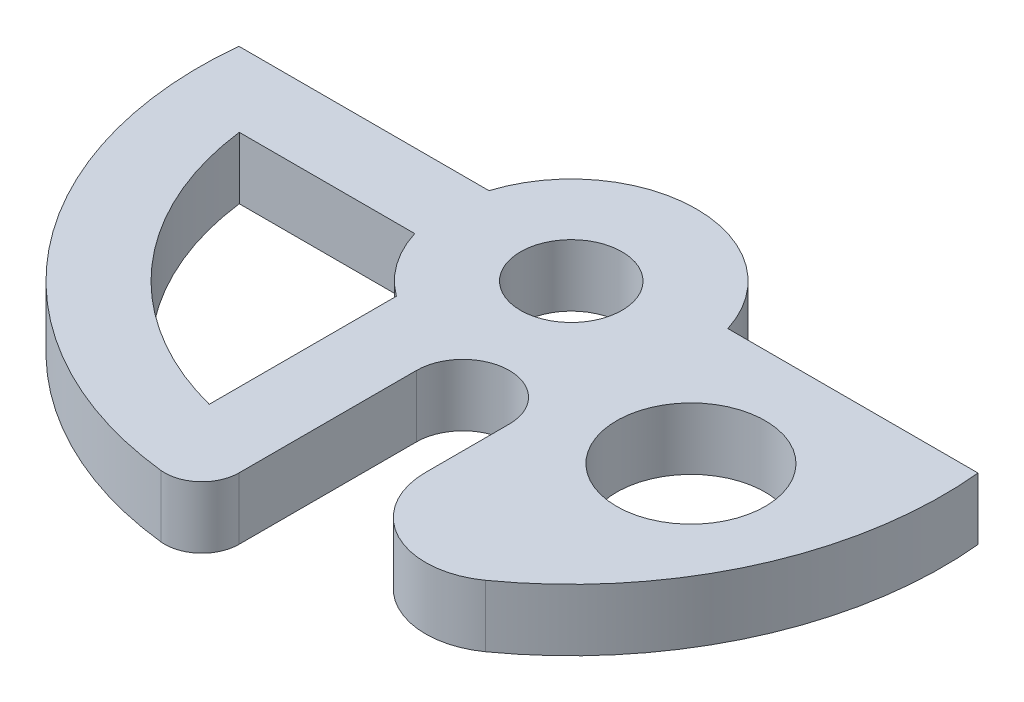
SolidWorks part; units mm, degrees
ref_plane "Front Plane" through (0, 0, 0) normal (0, 0, 1) x (1, 0, 0)
ref_plane "Top Plane" through (0, 0, 0) normal (0, 1, 0) x (1, 0, 0)
ref_plane "Right Plane" through (0, 0, 0) normal (1, 0, 0) x (0, 0, -1)
sketch "Sketch1" plane through (0, 0, 0) normal (0, 1, 0) x (1, 0, 0)
  line L0 (0, -12.5) -> (0, -30)
  line L1 (0, 0) -> (13.8, -19.2678) construction
  line L2 (0, 0) -> (0, -30) construction
  line L3 (7.5, -12.5) -> (7.5, -30)
  circle A0 centre (0, 0) radius 30
  circle A1 centre (13.8, -19.2678) radius 6.3
  circle A2 centre (3.75, -12.5) radius 3.75
  circle A3 centre (0, 0) radius 4.1
  dimension "D1" = 60
  dimension "D2" = 12.6
  dimension "D5" = 8.2
  dimension "D3" = 17.5
  dimension "D4" = 7.5
extrude "Boss-Extrude1" add sketch "Sketch1" along normal blind 5 contours A2 L3 A1 A0 L0 A3 | A1
fillet "Fillet1" radius 3 1 edges at (0, 2.5, 30)
sketch "Sketch2" plane through (0, 5, 0) normal (0, 1, 0) x (1, 0, 0)
  line L0 (0, -24) -> (0, -10.1)
  line L1 (-6, -24) -> (-6, -8.1247)
  line L2 (-6, -24) -> (-6, -10.1) construction
  line L3 (-24, 0) -> (24, 0) construction
  line L4 (-24, -3) -> (24, -3)
  line L5 (-24, 3) -> (24, 3)
  line L6 (24, 3) -> (35.1662, 3)
  line L7 (-24, 3) -> (-33.0695, 3)
  circle A0 centre (0, 0) radius 24
  circle A1 centre (0, 0) radius 10.1
  circle A2 centre (0, 0) radius 4.1 construction
  arc A3 (17.4684, -24.3897) -> (-3.3333, -29.8142) centre (0, 0) ccw construction
  arc A6 (17.4684, -24.3897) -> (-3.3333, -29.8142) centre (0, 0) ccw
  arc A7 (17.4684, -24.3897) -> (-3.3333, -29.8142) centre (0, 0) ccw
  arc M4 (17.4684, -24.3897) -> (-3.3333, -29.8142) centre (0, 0) ccw
  dimension "D1" = 6
  dimension "D2" = 6
  dimension "D3" = 6
  dimension "D4" = 3
  dimension "D5" = 3
  dimension "D6" = 0
extrude "Cut-Extrude1" cut sketch "Sketch2" against normal through all contours A0 L5 L6 L7 M4 | A1 L5 A0 | A1 L4 A0 L1
sketch "Sketch3" plane through (0, 5, 0) normal (0, 1, 0) x (1, 0, 0)
  circle A0 centre (17.5967, -7.9293) radius 6
  dimension "D1" = 12
extrude "Cut-Extrude2" cut sketch "Sketch3" against normal through all
